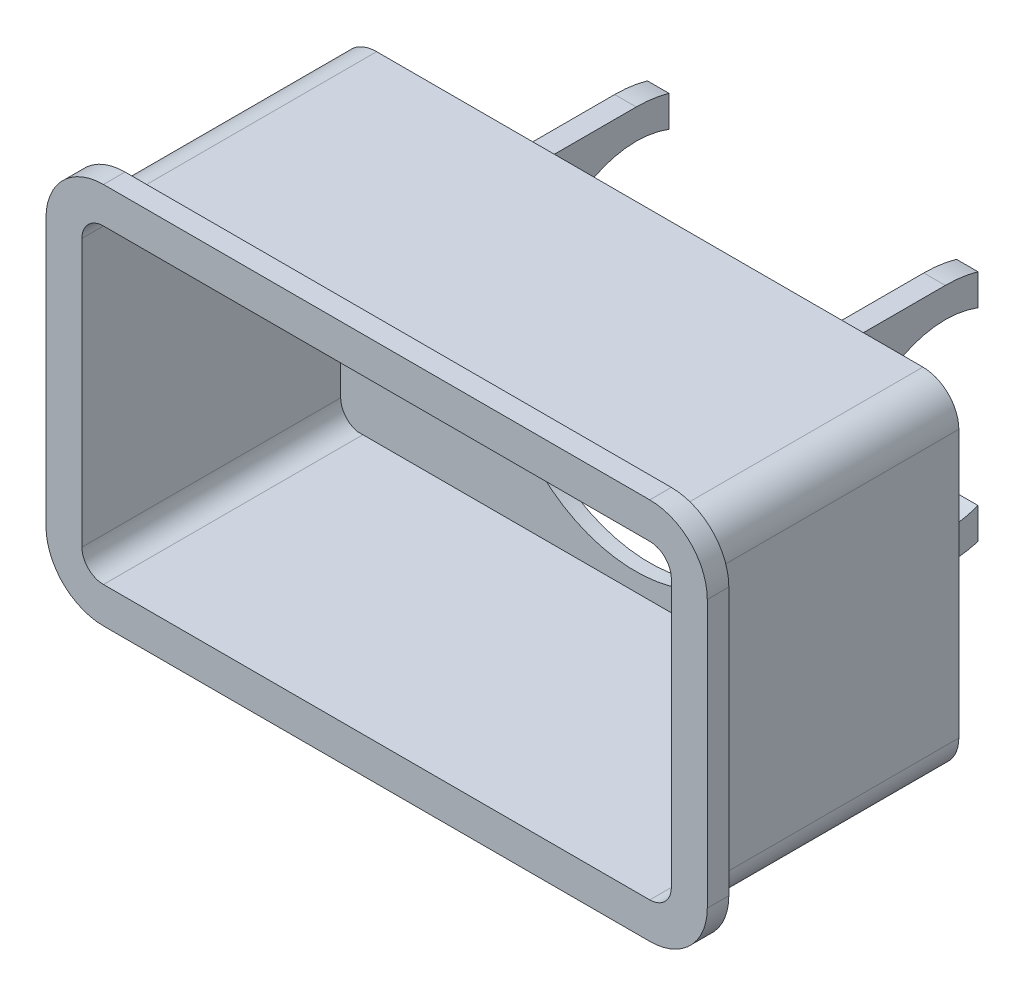
SolidWorks part; units mm, degrees
ref_plane "Front Plane" through (0, 0, 0) normal (0, 0, 1) x (1, 0, 0)
ref_plane "Top Plane" through (0, 0, 0) normal (0, 1, 0) x (1, 0, 0)
ref_plane "Right Plane" through (0, 0, 0) normal (1, 0, 0) x (0, 0, -1)
sketch "Sketch1" plane through (0, 0, 0) normal (0, 0, 1) x (1, 0, 0)
  line L0 (-38, 26.6) -> (38, 26.6)
  line L1 (-38, -23.6) -> (38, -23.6)
  line L2 (-43, -18.6) -> (-43, 18.6)
  line L3 (-38, 23.6) -> (38, 23.6)
  line L4 (43, -18.6) -> (43, 18.6)
  line L5 (46, -18.6) -> (46, 18.6)
  line L6 (-38, -26.6) -> (38, -26.6)
  line L7 (-46, -18.6) -> (-46, 18.6)
  arc A0 (43, 18.6) -> (38, 23.6) centre (38, 18.6) ccw
  arc A1 (38, -23.6) -> (43, -18.6) centre (38, -18.6) ccw
  arc A2 (-38, 23.6) -> (-43, 18.6) centre (-38, 18.6) ccw
  arc A3 (-43, -18.6) -> (-38, -23.6) centre (-38, -18.6) ccw
  arc A4 (46, 18.6) -> (38, 26.6) centre (38, 18.6) ccw
  arc A5 (38, -26.6) -> (46, -18.6) centre (38, -18.6) ccw
  arc A6 (-46, -18.6) -> (-38, -26.6) centre (-38, -18.6) ccw
  arc A7 (-38, 26.6) -> (-46, 18.6) centre (-38, 18.6) ccw
  point P0 (0, 0)
  dimension "D1" = 10
  dimension "D2" = 86
  dimension "D3" = 47.2
  dimension "D4" = 3
extrude "Boss-Extrude1" add sketch "Sketch1" along normal blind 3
sketch "Sketch2" plane through (0, 0, 3) normal (0, 0, 1) x (1, 0, 0)
  line L4 (-43, 18.6) -> (-43, -18.6)
  line L5 (-38, -23.6) -> (38, -23.6)
  line L6 (43, -18.6) -> (43, 18.6)
  line L7 (38, 23.6) -> (-38, 23.6)
  line L8 (-46, 18.6) -> (-46, -18.6)
  line L9 (-38, -26.6) -> (38, -26.6)
  line L10 (46, -18.6) -> (46, 18.6)
  line L11 (38, 26.6) -> (-38, 26.6)
  line L12 (-46, 18.6) -> (-46, -18.6)
  line L13 (-38, -26.6) -> (38, -26.6)
  line L14 (46, -18.6) -> (46, 18.6)
  line L15 (38, 26.6) -> (-38, 26.6)
  line L16 (-41, 18.6) -> (-41, -18.6)
  line L17 (-38, -21.6) -> (38, -21.6)
  line L18 (41, -18.6) -> (41, 18.6)
  line L19 (38, 21.6) -> (-38, 21.6)
  arc A4 (-38, 23.6) -> (-43, 18.6) centre (-38, 18.6) ccw
  arc A5 (-43, -18.6) -> (-38, -23.6) centre (-38, -18.6) ccw
  arc A6 (38, -23.6) -> (43, -18.6) centre (38, -18.6) ccw
  arc A7 (43, 18.6) -> (38, 23.6) centre (38, 18.6) ccw
  arc A8 (-38, 26.6) -> (-46, 18.6) centre (-38, 18.6) ccw
  arc A9 (-46, -18.6) -> (-38, -26.6) centre (-38, -18.6) ccw
  arc A10 (38, -26.6) -> (46, -18.6) centre (38, -18.6) ccw
  arc A11 (46, 18.6) -> (38, 26.6) centre (38, 18.6) ccw
  arc A12 (-38, 26.6) -> (-46, 18.6) centre (-38, 18.6) ccw
  arc A13 (-46, -18.6) -> (-38, -26.6) centre (-38, -18.6) ccw
  arc A14 (38, -26.6) -> (46, -18.6) centre (38, -18.6) ccw
  arc A15 (46, 18.6) -> (38, 26.6) centre (38, 18.6) ccw
  arc A16 (-38, 21.6) -> (-41, 18.6) centre (-38, 18.6) ccw
  arc A17 (-41, -18.6) -> (-38, -21.6) centre (-38, -18.6) ccw
  arc A18 (38, -21.6) -> (41, -18.6) centre (38, -18.6) ccw
  arc A19 (41, 18.6) -> (38, 21.6) centre (38, 18.6) ccw
  line M33 (43, 18.6) -> (43, -18.6)
  arc M34 (43, -18.6) -> (38, -23.6) centre (38, -18.6) cw
  line M35 (38, -23.6) -> (-38, -23.6)
  arc M36 (-38, -23.6) -> (-43, -18.6) centre (-38, -18.6) cw
  line M37 (-43, -18.6) -> (-43, 18.6)
  arc M38 (-43, 18.6) -> (-38, 23.6) centre (-38, 18.6) cw
  line M39 (-38, 23.6) -> (38, 23.6)
  arc M40 (38, 23.6) -> (43, 18.6) centre (38, 18.6) cw
  dimension "D1" = 0
  dimension "D2" = 3
  dimension "D3" = 2
extrude "Boss-Extrude2" add sketch "Sketch2" against normal blind 38 contours A19 L18 A18 L17 A17 L16 A16 L19 M33 M40 M39 M38 M37 M36 M35 M34
sketch "Sketch3" plane through (0, 0, -35) normal (0, 0, -1) x (-1, 0, 0)
  line L1 (41, 21.6) -> (-41, 21.6)
  line L2 (41, 21.6) -> (41, -21.5094)
  line L3 (41, -21.5094) -> (-41, -21.5094)
  line L4 (-41, 21.6) -> (-41, -21.5094)
  circle A0 centre (0, 0) radius 19
  spline S0 degree 3 poles (-17.8072, -0.0016) (-17.8073, -35.0016) (17.1927, -35.0016) (17.1928, -0.0016) (17.1928, 34.9984) (-17.8072, 34.9984) (-17.8072, -0.0016) (-17.8073, -35.0016) (17.1927, -35.0016) knots -0.5 0 0 0 0.5 0.5 0.5 1 1 1 1.5 1.5 1.5 weights 1 0.333333 0.333333 1 0.333333 0.333333 1 0.333333 0.333333 only from (-17.8072, -0.0016) to (-17.8072, -0.0016) construction
  spline S1 degree 3 poles (-17.8072, -0.0016) (-17.8073, -35.0016) (17.1927, -35.0016) (17.1928, -0.0016) (17.1928, 34.9984) (-17.8072, 34.9984) (-17.8072, -0.0016) (-17.8073, -35.0016) (17.1927, -35.0016) knots -0.5 0 0 0 0.5 0.5 0.5 1 1 1 1.5 1.5 1.5 weights 1 0.333333 0.333333 1 0.333333 0.333333 1 0.333333 0.333333 only from (-17.8072, -0.0016) to (-17.8072, -0.0016)
  arc M5 (-41, 18.6) -> (-38, 21.6) centre (-38, 18.6) cw
  line M6 (-38, 21.6) -> (38, 21.6)
  arc M7 (38, 21.6) -> (41, 18.6) centre (38, 18.6) cw
  line M8 (41, 18.6) -> (41, -18.6)
  arc M9 (41, -18.6) -> (38, -21.6) centre (38, -18.6) cw
  arc M11 (-38, -21.6) -> (-41, -18.6) centre (-38, -18.6) cw
  line M12 (-41, -18.6) -> (-41, 18.6)
  dimension "D1" = 38
extrude "Boss-Extrude3" add sketch "Sketch3" against normal blind 2 contours L3 A0 M9 M8 M7 M6 M5 M12 M11
sketch "Sketch4" plane through (0, 0, -35) normal (0, 0, -1) x (-1, 0, 0)
  line L0 (38, 23.6) -> (-38, 23.6) construction
  line L1 (-23, 23.6) -> (-20, 23.6)
  line L2 (-23, 23.6) -> (-23, -18.4)
  line L3 (-23, -18.4) -> (-20, -18.4)
  line L4 (-20, 23.6) -> (-20, -18.4)
  line L7 (20, 23.6) -> (23, 23.6)
  line L8 (20, 23.6) -> (20, -18.4)
  line L9 (20, -18.4) -> (23, -18.4)
  line L10 (23, 23.6) -> (23, -18.4)
  line L11 (43, -18.6) -> (43, 18.6) construction
  line L12 (-43, 18.6) -> (-43, -18.6) construction
  dimension "D1" = 3
  dimension "D2" = 3
  dimension "D3" = 20
  dimension "D4" = 20
  dimension "D5" = 42
  dimension "D6" = 42
extrude "Boss-Extrude4" add sketch "Sketch4" along normal blind 35
sketch "Sketch5" plane through (-23, 0, 0) normal (-1, 0, 0) x (0, 0, 1)
  line L4 (-35, -18.4) -> (-35, 23.6)
  line L5 (-35, 23.6) -> (-70, 23.6)
  line L6 (-70, 23.6) -> (-70, -18.4)
  line L7 (-70, -18.4) -> (-35, -18.4)
  line L8 (-35, -18.4) -> (-35, 23.6)
  line L9 (-35, 23.6) -> (-70, 23.6)
  line L10 (-70, 23.6) -> (-70, -18.4)
  line L11 (-70, -18.4) -> (-35, -18.4)
  circle A0 centre (-53.122, 0) radius 12.75 construction
  circle A1 centre (-53.122, 0) radius 12.75
  dimension "D1" = 0
extrude "Cut-Extrude1" cut sketch "Sketch5" against normal up to vertex contours A1
sketch "Sketch6" plane through (-23, 0, 0) normal (-1, 0, 0) x (0, 0, 1)
  line L0 (-53.122, 16.878) -> (-35, 16.878)
  line L1 (-35, -18.4) -> (-35, 23.6) construction
  line L3 (-35, -16.878) -> (-53.122, -16.878)
  line L4 (-35, 16.878) -> (-35, 23.6)
  line L5 (-35, 23.6) -> (-70, 23.6)
  line L6 (-70, 23.6) -> (-70, -18.4)
  line L7 (-70, -18.4) -> (-35, -18.4)
  line L8 (-35, -18.4) -> (-35, -16.878)
  arc A0 (-53.122, 16.878) -> (-53.122, -16.878) centre (-53.122, 0) ccw
  line M6 (-35, -18.4) -> (-35, 23.6)
  line M7 (-35, 23.6) -> (-70, 23.6)
  line M8 (-70, 23.6) -> (-70, -18.4)
  line M9 (-70, -18.4) -> (-35, -18.4)
extrude "Cut-Extrude2" cut sketch "Sketch6" against normal up to surface (46 mm away) contours A0 L6 L3 M9 M6 | A0 L0 M6 M7 M8 up to face at (23, -12.75, -53.122)
sketch "Sketch7" plane through (-23, 0, 0) normal (-1, 0, 0) x (0, 0, 1)
  line L0 (-57.6669, 16.878) -> (-57.6669, -16.878)
  line L1 (-57.6669, -16.878) -> (-72.2492, -16.878)
  line L2 (-72.2492, -16.878) -> (-72.2492, 16.878)
  line L3 (-72.2492, 16.878) -> (-57.6669, 16.878)
extrude "Cut-Extrude3" cut sketch "Sketch7" against normal up to surface (46 mm away) up to face at (23, -12.75, -53.122)
sketch "Sketch8" plane through (0, 0, 3) normal (0, 0, 1) x (1, 0, 0)
  line L0 (-46, 18.6) -> (-46, -18.6) construction
  line L1 (-51, -31.6) -> (51, -31.6)
  line L2 (-51, -31.6) -> (-51, 31.6)
  line L3 (-51, 31.6) -> (51, 31.6)
  line L4 (51, -31.6) -> (51, 31.6)
  line L5 (-51, -31.6) -> (51, 31.6) construction
  line L6 (-51, 31.6) -> (51, -31.6) construction
  line L7 (38, 26.6) -> (-38, 26.6) construction
  point P0 (0, 0)
  dimension "D1" = 5
  dimension "D2" = 5
